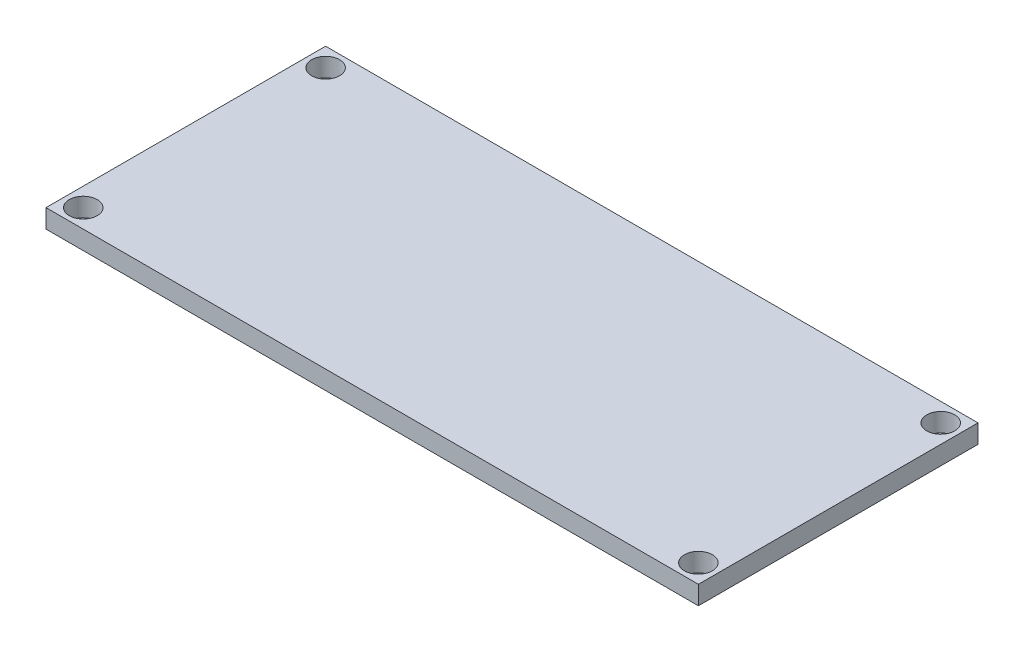
SolidWorks part; units mm, degrees
ref_plane "前视基准面" through (0, 0, 0) normal (0, 0, 1) x (1, 0, 0)
ref_plane "上视基准面" through (0, 0, 0) normal (0, 1, 0) x (1, 0, 0)
ref_plane "右视基准面" through (0, 0, 0) normal (1, 0, 0) x (0, 0, -1)
sketch "草图1" plane through (0, 0, 0) normal (0, 1, 0) x (1, 0, 0)
  line L1 (0, 0) -> (70, 0)
  line L2 (0, 0) -> (0, -30)
  line L3 (0, -30) -> (70, -30)
  line L4 (70, 0) -> (70, -30)
  circle A0 centre (2, -2) radius 1.5
  circle A1 centre (68, -2) radius 1.5
  circle A2 centre (2, -28) radius 1.5
  circle A3 centre (68, -28) radius 1.5
  dimension "D3" = 3
  dimension "D1" = 70
  dimension "D2" = 30
  dimension "D4" = 2
  dimension "D5" = 2
  dimension "D6" = 2
  dimension "D7" = 2
extrude "凸台-拉伸1" add sketch "草图1" along normal blind 2 contours L4 L1 L2 L3 A3 A2 A1 A0
